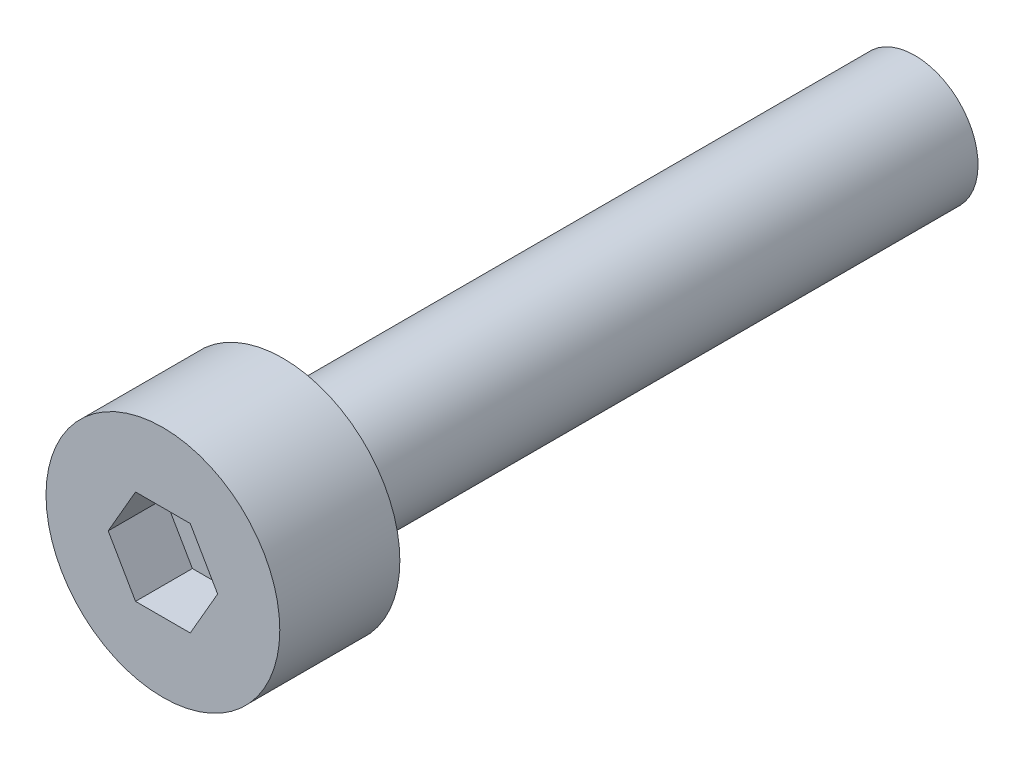
SolidWorks part; units mm, degrees
material "普通碳钢"
ref_plane "前视基准面" through (0, 0, 0) normal (0, 0, 1) x (1, 0, 0)
ref_plane "上视基准面" through (0, 0, 0) normal (0, 1, 0) x (1, 0, 0)
ref_plane "右视基准面" through (0, 0, 0) normal (1, 0, 0) x (0, 0, -1)
sketch "草图1" plane through (0, 0, 0) normal (1, 0, 0) x (0, 0, -1)
  line L0 (0, 0) -> (0, 1.85)
  line L1 (0, 1.85) -> (1.9, 1.85)
  line L2 (1.9, 1.85) -> (1.9, 1)
  line L3 (1.9, 1) -> (11.9, 1)
  line L4 (11.9, 1) -> (11.9, 0)
  line L5 (11.9, 0) -> (0, 0) construction
  line L6 (0, 0) -> (11.9, 0)
  dimension "D1" = 3.7
  dimension "D2" = 2
  dimension "D3" = 1.9
  dimension "D4" = 10
revolve "旋转1" add sketch "草图1" angle 360 about L5
cosmetic thread "装饰螺纹线1" parameters "D1"=3.18, "D2"=1.6
sketch "草图2" plane through (0, 0, 0) normal (0, 0, 1) x (1, 0, 0)
  line L1 (0.433, 0.75) -> (-0.433, 0.75)
  line L2 (-0.433, 0.75) -> (-0.866, 0)
  line L3 (-0.866, 0) -> (-0.433, -0.75)
  line L4 (-0.433, -0.75) -> (0.433, -0.75)
  line L5 (0.433, -0.75) -> (0.866, 0)
  line L6 (0.866, 0) -> (0.433, 0.75)
  circle A0 centre (0, 0) radius 0.75 construction
  dimension "D1" = 1.5
extrude "切除-拉伸1" cut sketch "草图2" against normal blind 0.9
